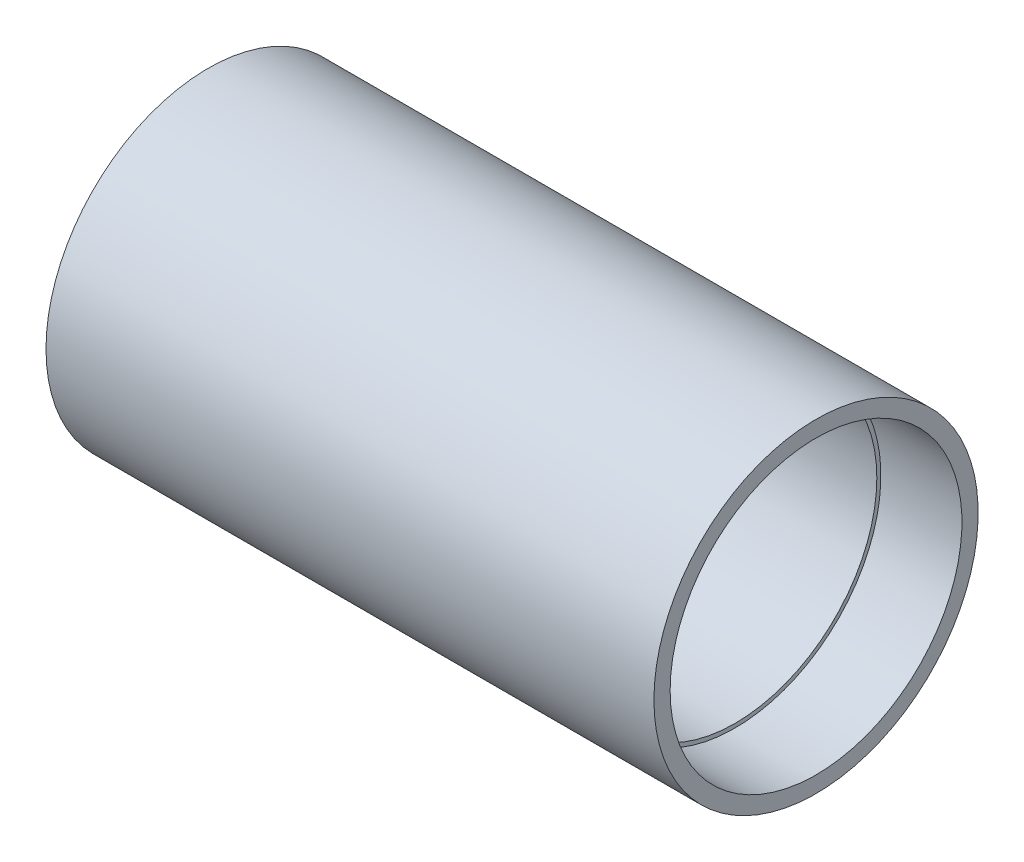
SolidWorks part; units mm, degrees
ref_plane "Ön Düzlem" through (0, 0, 0) normal (0, 0, 1) x (1, 0, 0)
ref_plane "Üst Düzlem" through (0, 0, 0) normal (0, 1, 0) x (1, 0, 0)
ref_plane "Sağ Düzlem" through (0, 0, 0) normal (1, 0, 0) x (0, 0, -1)
ref_axis "Eksen1" through (-88.99, 0, 0) along (1, 0, 0)
sketch "Çizim1" plane through (0, 0, 0) normal (0, 0, 1) x (1, 0, 0)
  line L3 (-150, 40) -> (0, 40)
  line L4 (0, 40) -> (0, 36)
  line L5 (0, 36) -> (-20, 36)
  line L6 (-20, 36) -> (-20, 35)
  line L7 (-20, 35) -> (-130, 35)
  line L8 (-130, 35) -> (-130, 36)
  line L9 (-130, 36) -> (-150, 36)
  line L10 (-150, 36) -> (-150, 40)
revolve "Döndür1" add sketch "Çizim1" angle 360 about axis through (-88.99, 0, 0) along (1, 0, 0)
